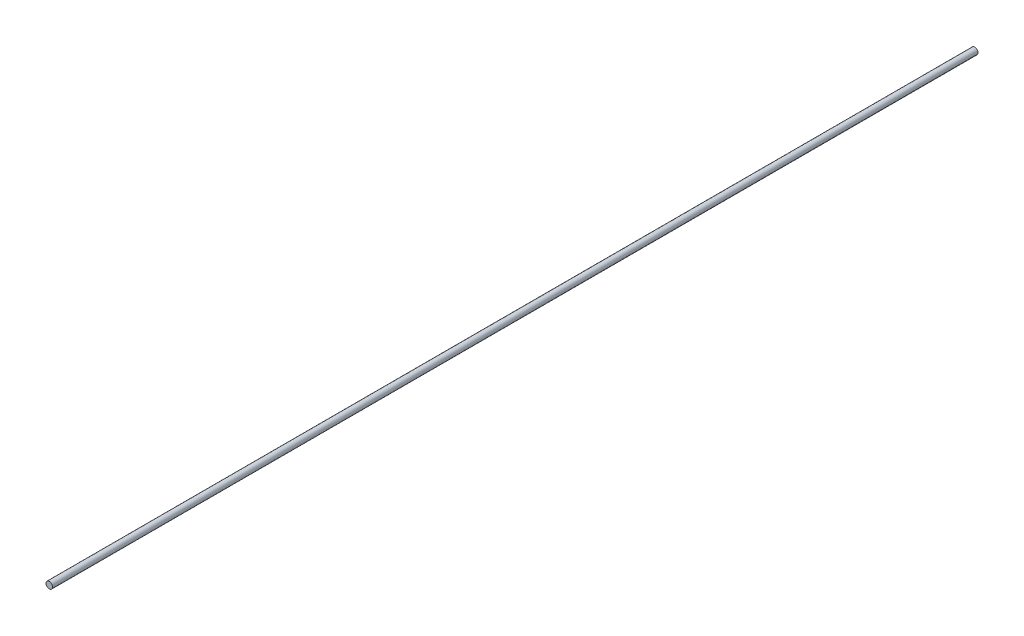
SolidWorks part; units mm, degrees
material "AISI 1020"
ref_plane "Front Plane" through (0, 0, 0) normal (0, 0, 1) x (1, 0, 0)
ref_plane "Top Plane" through (0, 0, 0) normal (0, 1, 0) x (1, 0, 0)
ref_plane "Right Plane" through (0, 0, 0) normal (1, 0, 0) x (0, 0, -1)
sketch "Sketch1" plane through (0, 0, 0) normal (0, 0, 1) x (1, 0, 0)
  circle A0 centre (0, 0) radius 7.9375
  dimension "D1" = 15.875
extrude "Boss-Extrude1" add sketch "Sketch1" along normal blind 2254.25
